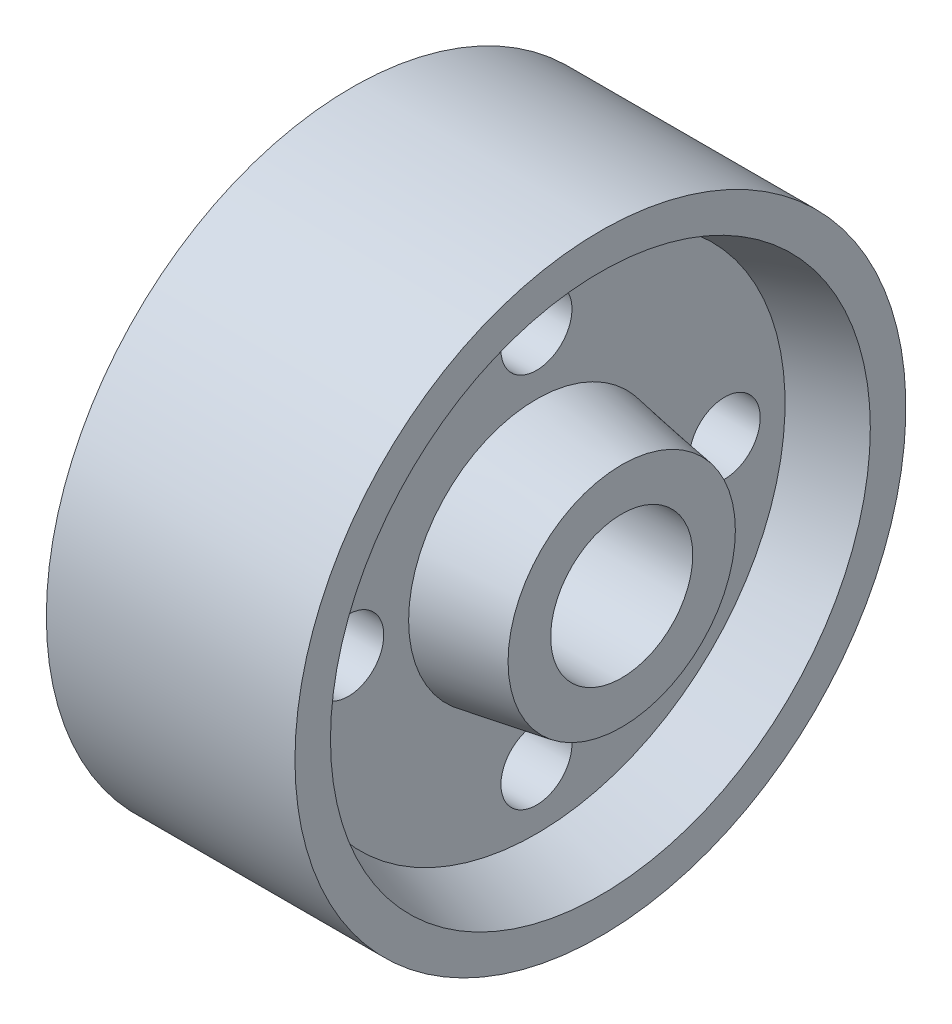
SolidWorks part; units mm, degrees
ref_plane "Front Plane" through (0, 0, 0) normal (0, 0, 1) x (1, 0, 0)
ref_plane "Top Plane" through (0, 0, 0) normal (0, 1, 0) x (1, 0, 0)
ref_plane "Right Plane" through (0, 0, 0) normal (1, 0, 0) x (0, 0, -1)
sketch "Sketch1" plane through (0, 0, 0) normal (0, 1, 0) x (1, 0, 0)
  line L0 (0, 0) -> (72.3466, 0) construction
  line L1 (0, 0) -> (0, 16)
  line L2 (0, 16) -> (12, 18)
  line L3 (12, 18) -> (12, 35)
  line L4 (12, 35) -> (3, 38)
  line L5 (3, 38) -> (3, 43)
  line L6 (3, 43) -> (38, 43)
  line L7 (20.5, 43) -> (20.5, 0) construction
  line L8 (41, 0) -> (41, 16)
  line L9 (41, 16) -> (29, 18)
  line L10 (29, 18) -> (29, 35)
  line L11 (29, 35) -> (38, 38)
  line L12 (38, 38) -> (38, 43)
  line L13 (0, 0) -> (41, 0)
  point P9 (0, 0)
  point P11 (0, 0)
  dimension "D1" = 32
  dimension "D2" = 36
  dimension "D3" = 70
  dimension "D4" = 76
  dimension "D5" = 86
  dimension "D6" = 12
  dimension "D7" = 20.5
  dimension "D8" = 17.5
revolve "Revolve3" add sketch "Sketch1" angle 360 about L0
sketch "Sketch4" plane through (12, 0, 0) normal (-1, 0, 0) x (0, 0, 1)
  circle A0 centre (0, 0) radius 26.5 construction
  circle A1 centre (0, 26.5) radius 5
  circle A2 centre (26.5, 0) radius 5
  circle A3 centre (0, -26.5) radius 5
  circle A4 centre (-26.5, 0) radius 5
  point P14 (0, 0)
  dimension "D1" = 53
  dimension "D2" = 10
  dimension "D3" = 4
extrude "Cut-Extrude4" cut sketch "Sketch4" against normal through all
sketch "Sketch6" plane through (41, 0, 0) normal (1, 0, 0) x (0, 0, -1)
  circle A0 centre (0, 0) radius 10
  dimension "D1" = 20
extrude "Cut-Extrude5" cut sketch "Sketch6" against normal through all
